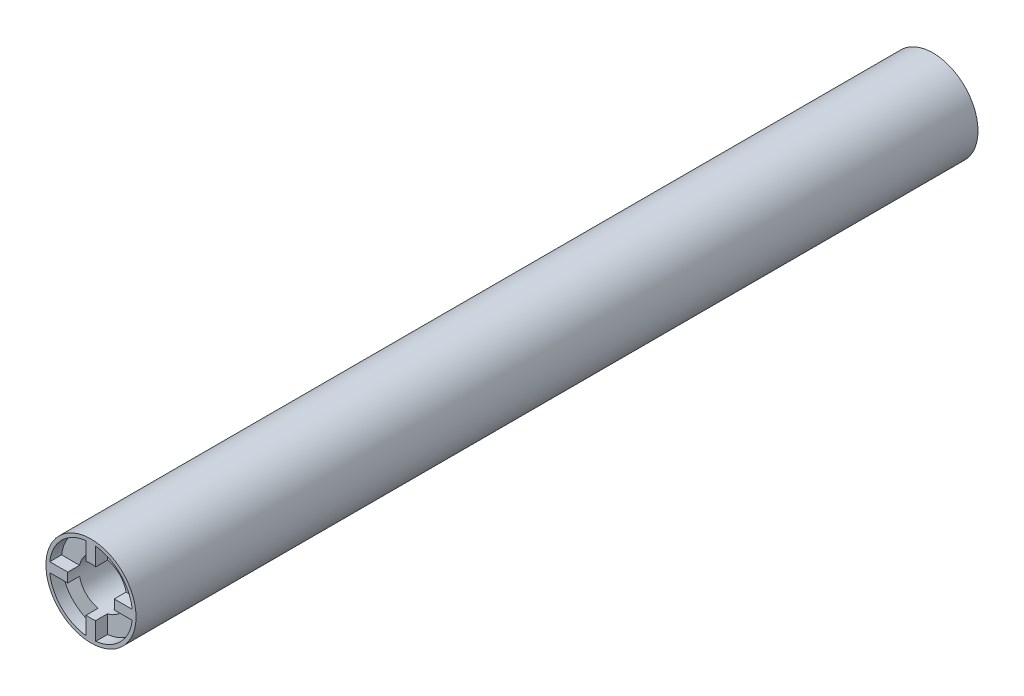
SolidWorks part; units mm, degrees
material "1.8901 (S460N)"
ref_plane "前视基准面" through (0, 0, 0) normal (0, 0, 1) x (1, 0, 0)
ref_plane "上视基准面" through (0, 0, 0) normal (0, 1, 0) x (1, 0, 0)
ref_plane "右视基准面" through (0, 0, 0) normal (1, 0, 0) x (0, 0, -1)
sketch "草图1" plane through (0, 0, 0) normal (0, 0, 1) x (1, 0, 0)
  circle A0 centre (0, 0) radius 1.9
  dimension "D1" = 3.8
extrude "凸台-拉伸1" add sketch "草图1" against normal blind 35
sketch "草图2" [suppressed] plane through (0, 0, -37) normal (0, 0, -1) x (-1, 0, 0)
  circle A0 centre (0, 0) radius 1.95
sketch "草图3" plane through (0, 0, 0) normal (0, 0, 1) x (1, 0, 0)
  circle A0 centre (0, 0) radius 1
  dimension "D1" = 2
extrude "切除-拉伸1" cut sketch "草图3" against normal blind 8
sketch "草图4" plane through (0, 0, 0) normal (0, 0, 1) x (1, 0, 0)
  line L0 (0, 1.9) -> (0, -1.9) construction
  line L1 (-1.9, 0) -> (1.9, 0) construction
  line L2 (-1.8894, 0.2) -> (-0.9798, 0.2)
  line L3 (-1.8894, -0.2) -> (-0.9798, -0.2)
  line L4 (-0.2, 1.8894) -> (-0.2, 0.9798)
  line L5 (0.2, 1.8894) -> (0.2, 0.9798)
  line L6 (0.9798, 0.2) -> (1.8894, 0.2)
  line L7 (0.9798, -0.2) -> (1.8894, -0.2)
  line L10 (-0.2, -0.9798) -> (-0.2, -1.8894)
  line L11 (0.2, -0.9798) -> (0.2, -1.8894)
  circle A0 centre (0, 0) radius 1.9
  circle A1 centre (0, 0) radius 1.75
  circle A2 centre (0, 0) radius 1
  circle M10 centre (0, 0) radius 1
  circle M11 centre (0, 0) radius 1.9
  dimension "D1" = 2
  dimension "D2" = 3.8
  dimension "D3" = 3.5
  dimension "D4" = 0.2
  dimension "D5" = 0.2
  dimension "D6" = 0.2
  dimension "D7" = 0.2
extrude "凸台-拉伸3" add sketch "草图4" along normal blind 0.5 contours A1 L2 L3 M11 | A1 L7 L6 M11 | A1 L11 L7 M11 | A1 L10 L11 M11 | A1 L3 L10 M11 | A1 L4 L2 M11 | A1 L6 L5 M11 | A1 L5 L4 M11 | L2 A1 L3 M10 | L7 A1 L6 M10 | L5 A1 L4 M10 | L10 A1 L11 M10
